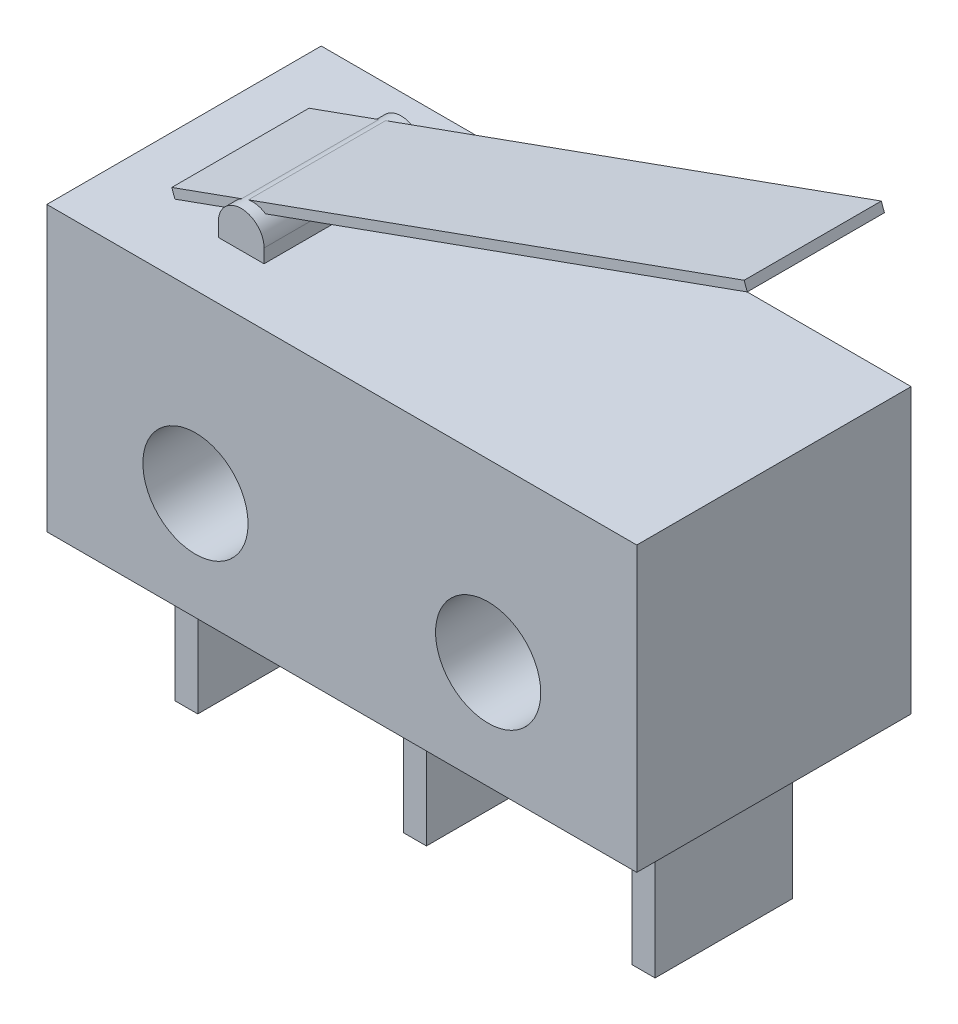
SolidWorks part; units mm, degrees
ref_plane "Plano frontal" through (0, 0, 0) normal (0, 0, 1) x (1, 0, 0)
ref_plane "Plano superior" through (0, 0, 0) normal (0, 1, 0) x (1, 0, 0)
ref_plane "Plano direito" through (0, 0, 0) normal (1, 0, 0) x (0, 0, -1)
sketch "Esboço1" plane through (0, 0, 0) normal (0, 0, 1) x (1, 0, 0)
  line L0 (0, 0) -> (0, 6.2)
  line L4 (-12.9, 6.2) -> (-12.9, 0)
  line L5 (-12.9, 0) -> (0, 0)
  line L6 (-12.9, 6.2) -> (0, 6.2)
  dimension "D1" = 6.2
  dimension "D2" = 12.9
extrude "Ressalto-extrusão1" add sketch "Esboço1" along normal blind 6
ref_plane "Plano1" through (0, 0, 3) normal (0, 0, 1) x (1, 0, 0)
sketch "Esboço3" plane through (0, 0, 3) normal (0, 0, 1) x (1, 0, 0)
  line L1 (-10.4, 6.2) -> (-9.4, 6.2)
  line L2 (-10.4, 6.2) -> (-10.4, 6.5)
  line L3 (-9.4, 6.5) -> (-9.4, 6.2)
  line L4 (0, 6.2) -> (-12.9, 6.2) construction
  arc A0 (-9.4, 6.5) -> (-10.4, 6.5) centre (-9.9, 6.5) ccw
  point P0 (0, 0)
  point P6 (0, 0)
  dimension "D3" = 0.5
extrude "Ressalto-extrusão2" add sketch "Esboço3" along normal mid plane 3.5
sketch "Esboço4" plane through (0, 0, 3) normal (0, 0, 1) x (1, 0, 0)
  line L0 (0, 0) -> (0, 6.2) construction
  line L1 (-12.9, 0) -> (0, 0) construction
  line L2 (-3.25, 2.35) -> (-21.6293, 2.35) construction
  line L3 (-12.9, 6.2) -> (-12.9, 0) construction
  circle A0 centre (-3.25, 2.35) radius 1.15
  circle A1 centre (-9.65, 2.35) radius 1.15
  dimension "D1" = 2.3
  dimension "D2" = 2.3
  dimension "D3" = 3.25
  dimension "D4" = 2.35
  dimension "D5" = 3.25
extrude "Corte-extrusão1" cut sketch "Esboço4" against normal through all both and the other way through all
sketch "Esboço5" plane through (0, 0, 0) normal (0, -1, 0) x (1, 0, 0)
  line L0 (-12.9, 6) -> (-12.9, 0) construction
  line L1 (-1.1, 4.5) -> (-1.6, 4.5)
  line L2 (-1.1, 4.5) -> (-1.1, 1.5)
  line L3 (-1.1, 1.5) -> (-1.6, 1.5)
  line L4 (-1.6, 4.5) -> (-1.6, 1.5)
  line L5 (-6.1, 4.5) -> (-6.6, 4.5)
  line L6 (-6.1, 4.5) -> (-6.1, 1.5)
  line L7 (-6.1, 1.5) -> (-6.6, 1.5)
  line L8 (-6.6, 4.5) -> (-6.6, 1.5)
  line L9 (-11.1, 4.5) -> (-11.6, 4.5)
  line L10 (-11.1, 4.5) -> (-11.1, 1.5)
  line L11 (-11.1, 1.5) -> (-11.6, 1.5)
  line L12 (-11.6, 4.5) -> (-11.6, 1.5)
  line L13 (-24.2475, 3) -> (2.7447, 3) construction
  line L14 (10.175, 3) -> (-10.175, 3) construction
  dimension "D1" = 1.3
  dimension "D2" = 0.5
  dimension "D3" = 0.5
  dimension "D4" = 0.5
  dimension "D5" = 4.5
  dimension "D6" = 4.5
  dimension "D7" = 3
  dimension "D8" = 1.5
extrude "Ressalto-extrusão3" add sketch "Esboço5" along normal blind 3.3
sketch "Esboço6" plane through (0, 0, 3) normal (0, 0, 1) x (1, 0, 0)
  line L0 (-11.6, 6.2) -> (0.9156, 10.7)
  line L1 (0, 6.2) -> (-12.9, 6.2) construction
  line L2 (-11.6, 6.2) -> (-11.6677, 6.3882)
  line L3 (-11.6677, 6.3882) -> (0.8479, 10.8882)
  line L4 (0.8479, 10.8882) -> (0.9156, 10.7)
  dimension "D1" = 1.3
  dimension "D2" = 13.3
  dimension "D3" = 4.5
  dimension "D4" = 0.2
extrude "Ressalto-extrusão8" add sketch "Esboço6" along normal mid plane 3 separate body
